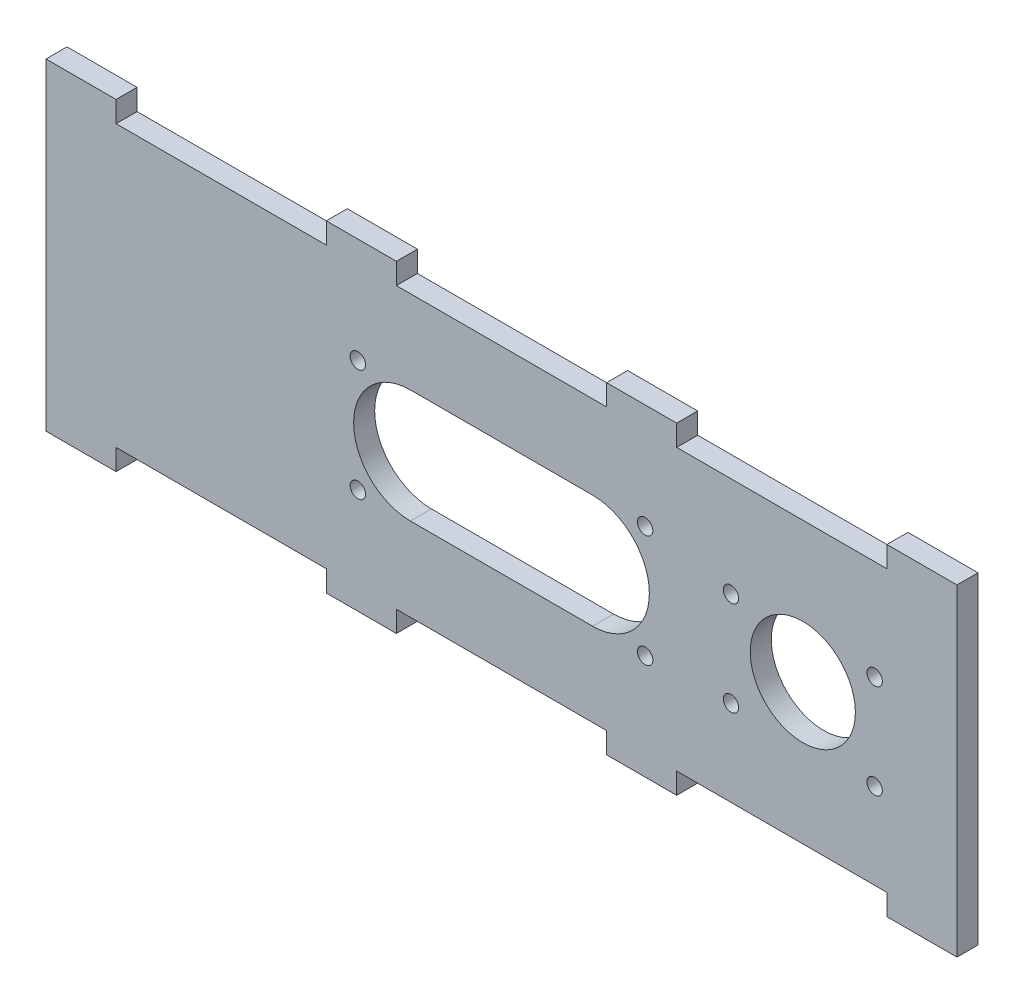
SolidWorks part; units mm, degrees
ref_plane "Front Plane" through (0, 0, 0) normal (0, 0, 1) x (1, 0, 0)
ref_plane "Top Plane" through (0, 0, 0) normal (0, 1, 0) x (1, 0, 0)
ref_plane "Right Plane" through (0, 0, 0) normal (1, 0, 0) x (0, 0, -1)
sketch "Sketch1" plane through (0, 0, 0) normal (0, 0, 1) x (1, 0, 0)
  line L0 (-65, 0) -> (65, 0) construction
  line L1 (-65, 20) -> (65, 20)
  line L2 (-65, 20) -> (-65, -20)
  line L3 (-65, -20) -> (65, -20)
  line L4 (65, 20) -> (65, -20)
  line L5 (-65, 20) -> (-55, 20)
  line L6 (-65, 20) -> (-65, 23)
  line L7 (-65, 23) -> (-55, 23)
  line L8 (-55, 20) -> (-55, 23)
  line L9 (65, 20) -> (55, 20)
  line L10 (65, 20) -> (65, 23)
  line L11 (65, 23) -> (55, 23)
  line L12 (55, 20) -> (55, 23)
  line L13 (-25, 20) -> (-15, 20)
  line L14 (-25, 20) -> (-25, 23)
  line L15 (-25, 23) -> (-15, 23)
  line L16 (-15, 20) -> (-15, 23)
  line L17 (25, 20) -> (15, 20)
  line L18 (25, 20) -> (25, 23)
  line L19 (25, 23) -> (15, 23)
  line L20 (15, 20) -> (15, 23)
  line L21 (65, -23) -> (55, -23)
  line L22 (55, -20) -> (55, -23)
  line L23 (65, -20) -> (55, -20)
  line L24 (65, -20) -> (65, -23)
  line L25 (25, -23) -> (15, -23)
  line L26 (15, -20) -> (15, -23)
  line L27 (25, -20) -> (15, -20)
  line L28 (25, -20) -> (25, -23)
  line L29 (-25, -23) -> (-15, -23)
  line L30 (-15, -20) -> (-15, -23)
  line L31 (-25, -20) -> (-15, -20)
  line L32 (-25, -20) -> (-25, -23)
  line L33 (-65, -23) -> (-55, -23)
  line L34 (-55, -20) -> (-55, -23)
  line L35 (-65, -20) -> (-55, -20)
  line L36 (-65, -20) -> (-65, -23)
  circle A8 centre (32.75, 5.75) radius 1.1 construction
  circle A9 centre (32.75, -7.75) radius 1.1 construction
  circle A10 centre (53.25, -7.75) radius 1.1 construction
  circle A11 centre (53.25, 5.75) radius 1.1 construction
  circle A12 centre (32.75, 5.75) radius 1.1
  circle A13 centre (32.75, -7.75) radius 1.1
  circle A14 centre (53.25, -7.75) radius 1.1
  circle A15 centre (53.25, 5.75) radius 1.1
  point P4 (0, 20)
  point P6 (-65, 0)
  point P21 (-60, 23)
  point P22 (-20, 23)
  point P23 (60, 23)
  point P24 (20, 23)
  dimension "D1" = 40
  dimension "D2" = 130
  dimension "D3" = 10
  dimension "D4" = 3
  dimension "D5" = 40
  dimension "D6" = 40
extrude "Boss-Extrude1" add sketch "Sketch1" along normal blind 3 contours L2 L0 L4 L1 | L0 L2 L3 L4 | L1 L8 L7 L6 | L1 L16 L15 L14 | L20 L1 L18 L19 | L12 L1 L10 L11 | L24 L3 L22 L21 | L28 L3 L26 L25 | L3 L32 L29 L30 | L3 L36 L33 L34
sketch "Sketch4" plane through (0, 0, 3) normal (0, 0, 1) x (1, 0, 0)
  point P0 (0, 0)
  line B0 (-13, 8.1) -> (13, 8.1)
  line B1 (-13, -8.1) -> (13, -8.1)
  arc B2 (-13, 8.1) -> (-13, -8.1) centre (-13, 0) ccw
  arc B3 (13, -8.1) -> (13, 8.1) centre (13, 0) ccw
  circle B4 centre (-20.5, 8) radius 1.1
  circle B5 centre (-20.5, -8) radius 1.1
  circle B6 centre (20.5, 8) radius 1.1
  circle B7 centre (20.5, -8) radius 1.1
sketch_block_instance "Block-SRF05-1"
sketch_block "Block1" parameters "D4"=16.2, "D5"=2.2, "D1"=45, "D2"=20, "D3"=26, "D6"=2, "D7"=2, "D8"=2, "D9"=2
extrude "Cut-Extrude2" cut sketch "Sketch4" against normal through all
sketch "Sketch5" plane through (0, 0, 3) normal (0, 0, 1) x (1, 0, 0)
  line L0 (65, 23) -> (65, -23) construction
  circle A0 centre (43, 0) radius 7.5
  dimension "D1" = 15
  dimension "D2" = 22
extrude "Cut-Extrude3" cut sketch "Sketch5" against normal through all
